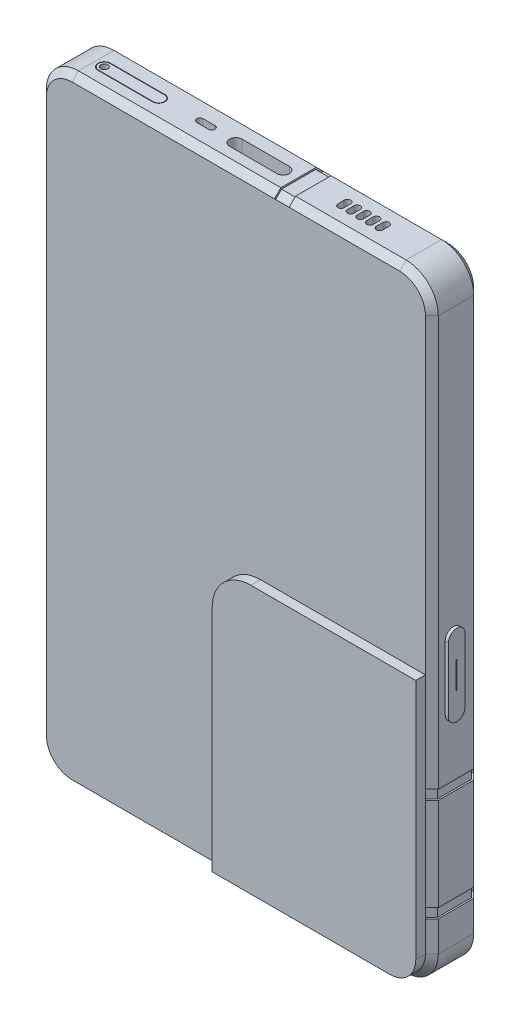
SolidWorks part; units mm, degrees
ref_plane "前视基准面" through (0, 0, 0) normal (0, 0, 1) x (1, 0, 0)
ref_plane "上视基准面" through (0, 0, 0) normal (0, 1, 0) x (1, 0, 0)
ref_plane "右视基准面" through (0, 0, 0) normal (1, 0, 0) x (0, 0, -1)
other "Configuration Table"
sketch "草图1" plane through (0, 0, 0) normal (0, 0, 1) x (1, 0, 0)
  line L1 (-50.8752, 95.8479) -> (50.8752, 95.8479)
  line L2 (-60.8752, 85.8479) -> (-60.8752, -85.8479)
  line L3 (-50.8752, -95.8479) -> (50.8752, -95.8479)
  line L4 (60.8752, 85.8479) -> (60.8752, -85.8479)
  line L5 (-60.8752, 95.8479) -> (60.8752, -95.8479) construction
  line L6 (-60.8752, -95.8479) -> (60.8752, 95.8479) construction
  arc A0 (60.8752, -85.8479) -> (50.8752, -95.8479) centre (50.8752, -85.8479) cw
  arc A1 (-50.8752, -95.8479) -> (-60.8752, -85.8479) centre (-50.8752, -85.8479) cw
  arc A2 (60.8752, 85.8479) -> (50.8752, 95.8479) centre (50.8752, 85.8479) ccw
  arc A3 (-60.8752, 85.8479) -> (-50.8752, 95.8479) centre (-50.8752, 85.8479) cw
  point P0 (0, 0)
  dimension "D1" = 10
extrude "凸台-拉伸1" add sketch "草图1" along normal blind 15
sketch "草图4" plane through (0, 95.8479, 0) normal (0, 1, 0) x (1, 0, 0)
  line L4 (25.1849, -6.5259) -> (25.1849, -8.5259)
  line L5 (27.1849, -6.5259) -> (27.1849, -8.5259)
  arc A0 (27.1849, -6.5259) -> (25.1849, -6.5259) centre (26.1849, -6.5259) ccw
  arc A1 (25.1849, -8.5259) -> (27.1849, -8.5259) centre (26.1849, -8.5259) ccw
  dimension "D1" = 2
  dimension "D2" = 2
chamfer "倒角7" distance 2 angle 45 8 edges at (60.8752, 0, 0) (57.9463, 92.919, 0) (0, 95.8479, 0) (-57.9463, 92.919, 0) (-60.8752, 0, 0) (-57.9463, -92.919, 0) (0, -95.8479, 0) (57.9463, -92.919, 0)
chamfer "倒角8" distance 2 angle 45 8 edges at (0, -95.8479, 15) (-57.9463, -92.919, 15) (-60.8752, 0, 15) (-57.9463, 92.919, 15) (0, 95.8479, 15) (57.9463, 92.919, 15) (60.8752, 0, 15) (57.9463, -92.919, 15)
extrude "切除-拉伸1" cut sketch "草图4" against normal blind 6
pattern_linear "阵列(线性)1" count 5 spacing 3 along (1, 0, 0) of "切除-拉伸1"
sketch "草图5" plane through (0, 95.8479, 0) normal (0, 1, 0) x (1, 0, 0)
  line L0 (-18.6749, -6.5259) -> (-14.9566, -6.5259)
  line L1 (-18.6749, -8.5259) -> (-14.9566, -8.5259)
  arc A0 (-18.6749, -6.5259) -> (-18.6749, -8.5259) centre (-18.6749, -7.5259) ccw
  arc A1 (-14.9566, -8.5259) -> (-14.9566, -6.5259) centre (-14.9566, -7.5259) ccw
extrude "切除-拉伸2" cut sketch "草图5" against normal blind 10
sketch "草图6" plane through (0, 95.8479, 0) normal (0, 1, 0) x (1, 0, 0)
  line L0 (-7.0941, -5.9549) -> (7.6008, -5.9549)
  line L1 (-7.0941, -9.8398) -> (7.6008, -9.8398)
  arc A0 (7.6008, -9.8398) -> (7.6008, -5.9549) centre (7.6008, -7.8973) ccw
  arc A1 (-7.0941, -5.9549) -> (-7.0941, -9.8398) centre (-7.0941, -7.8973) ccw
extrude "切除-拉伸3" cut sketch "草图6" against normal blind 40
sketch "草图7" plane through (0, 95.8479, 0) normal (0, 1, 0) x (1, 0, 0)
  line L0 (-47.9434, -5.9549) -> (-31.0508, -5.9549)
  line L2 (-47.9434, -9.8398) -> (-31.0508, -9.8398)
  arc A0 (-47.9434, -5.9549) -> (-47.9434, -9.8398) centre (-47.9434, -7.8973) ccw
  arc A2 (-31.0508, -9.8398) -> (-31.0508, -5.9549) centre (-31.0508, -7.8973) ccw
extrude "切除-拉伸5" cut sketch "草图7" against normal blind 20
sketch "草图8" plane through (0, 75.8479, 0) normal (0, 1, 0) x (1, 0, 0)
  line L0 (-47.9434, -6.108) -> (-31.0508, -6.108)
  line L2 (-31.0508, -5.9549) -> (-47.9434, -5.9549) construction
  line L3 (-47.9434, -9.6898) -> (-31.0508, -9.6898)
  line L4 (-47.9434, -9.8398) -> (-31.0508, -9.8398) construction
  arc A0 (-47.9434, -6.108) -> (-47.9434, -9.6898) centre (-47.9434, -7.8989) ccw
  arc A1 (-31.0508, -9.6898) -> (-31.0508, -6.108) centre (-31.0508, -7.8989) ccw
  dimension "D1" = 0.1531
  dimension "D2" = 0.15
extrude "凸台-拉伸2" add sketch "草图8" along normal blind 20
sketch "草图9" plane through (0, 95.8479, 0) normal (0, 1, 0) x (1, 0, 0)
  circle A0 centre (-47.9434, -7.8989) radius 1.1146
extrude "切除-拉伸6" cut sketch "草图9" against normal blind 20
sketch "草图10" plane through (0, -95.8479, 0) normal (0, -1, 0) x (1, 0, 0)
  line L0 (50.8752, 15) -> (50.8752, 0) construction
  line L1 (50.8752, 7.5) -> (-60.3841, 7.5) construction
  line L4 (-8.9454, 10.4902) -> (-20.2688, 10.4902)
  line L5 (-8.9454, 4.5098) -> (-20.2688, 4.5098)
  circle A0 centre (47.885, 7.5) radius 2.9902
  arc A3 (-20.2688, 10.4902) -> (-20.2688, 4.5098) centre (-20.2688, 7.5) ccw
  arc A4 (-8.9454, 4.5098) -> (-8.9454, 10.4902) centre (-8.9454, 7.5) ccw
extrude "切除-拉伸8" cut sketch "草图10" against normal blind 20
sketch "草图12" plane through (0, 95.8479, 0) normal (0, 1, 0) x (1, 0, 0)
  line L0 (11.9924, -2) -> (11.9924, -13)
  line L1 (50.8752, -2) -> (-50.8752, -2) construction
  line L2 (-50.8752, -13) -> (50.8752, -13) construction
  line L3 (11.9924, -13) -> (16.5529, -13)
  line L4 (16.5529, -13) -> (16.5529, -2)
  line L5 (16.5529, -2) -> (11.9924, -2)
extrude "切除-拉伸9" cut sketch "草图12" against normal blind 0.5
sketch "草图13" plane through (0, 54.424, 54.424) normal (0, 0.7071, 0.7071) x (1, 0, 0)
  line L0 (11.9924, 58.5823) -> (11.9924, 55.7539)
  line L1 (50.8752, 55.7539) -> (-50.8752, 55.7539) construction
  line L2 (11.9924, 55.7539) -> (16.5529, 55.7539)
  line L3 (16.5529, 55.7539) -> (16.5529, 58.5823)
  line L4 (16.5529, 58.5823) -> (11.9924, 58.5823)
extrude "切除-拉伸10" cut sketch "草图13" against normal blind 0.5
sketch "草图14" plane through (0, 46.924, -46.924) normal (0, 0.7071, -0.7071) x (1, 0, 0)
  line L0 (11.9924, -69.1889) -> (11.9924, -66.3605)
  line L1 (-50.8752, -66.3605) -> (50.8752, -66.3605) construction
  line L2 (11.9924, -66.3605) -> (16.5529, -66.3605)
  line L3 (16.5529, -66.3605) -> (16.5529, -69.1889)
  line L4 (16.5529, -69.1889) -> (11.9924, -69.1889)
extrude "切除-拉伸11" cut sketch "草图14" against normal blind 0.5
sketch "草图15" plane through (60.8752, 0, 0) normal (1, 0, 0) x (0, 0, -1)
  line L0 (-10.8469, -2.6673) -> (-10.8469, -22.6286)
  line L1 (-5.6844, -2.6673) -> (-5.6844, -22.6286)
  arc A0 (-5.6844, -2.6673) -> (-10.8469, -2.6673) centre (-8.2657, -2.6673) ccw
  arc A1 (-10.8469, -22.6286) -> (-5.6844, -22.6286) centre (-8.2657, -22.6286) ccw
extrude "凸台-拉伸3" add sketch "草图15" along normal blind 1
sketch "草图16" plane through (61.8752, 0, 0) normal (1, 0, 0) x (0, 0, -1)
  line L0 (-8.2657, -0.086) -> (-8.2657, -25.2099) construction
  line L1 (-8.4657, -8.6479) -> (-8.4657, -16.6479)
  line L3 (-10.8469, -12.6479) -> (-5.6844, -12.6479) construction
  line L4 (-10.8469, -2.6673) -> (-10.8469, -22.6286) construction
  line L5 (-5.6844, -22.6286) -> (-5.6844, -2.6673) construction
  line L6 (-8.0657, -8.6479) -> (-8.0657, -16.6479)
  arc A0 (-5.6844, -2.6673) -> (-10.8469, -2.6673) centre (-8.2657, -2.6673) ccw construction
  arc A1 (-10.8469, -22.6286) -> (-5.6844, -22.6286) centre (-8.2657, -22.6286) ccw construction
  arc A2 (-8.0657, -8.6479) -> (-8.4657, -8.6479) centre (-8.2657, -8.6479) ccw
  arc A3 (-8.4657, -16.6479) -> (-8.0657, -16.6479) centre (-8.2657, -16.6479) ccw
  dimension "D1" = 4
  dimension "D2" = 4
  dimension "D3" = 0.2
  dimension "D4" = 0.2
extrude "凸台-拉伸4" add sketch "草图16" along normal blind 0.1
sketch "草图17" plane through (60.8752, 0, 0) normal (1, 0, 0) x (0, 0, -1)
  line L0 (-13, -73.3596) -> (-2, -73.3596)
  line L3 (-13, 85.8479) -> (-13, -85.8479) construction
  line L4 (-2, -85.8479) -> (-2, 85.8479) construction
  line L5 (-2, -73.3596) -> (-2, -76.3596)
  line L6 (-2, -76.3596) -> (-13, -76.3596)
  line L7 (-13, -76.3596) -> (-13, -73.3596)
  line L8 (-13, -41.5134) -> (-2, -41.5134)
  line L9 (-2, -41.5134) -> (-2, -44.5134)
  line L10 (-2, -44.5134) -> (-13, -44.5134)
  line L11 (-13, -44.5134) -> (-13, -41.5134)
  dimension "D1" = 3
  dimension "D2" = 3
extrude "切除-拉伸12" cut sketch "草图17" against normal blind 0.5
sketch "草图18" plane through (29.4376, 0, -29.4376) normal (0.7071, 0, -0.7071) x (-0.7071, 0, -0.7071)
  line L0 (-44.4595, -41.5134) -> (-41.6311, -41.5134)
  line L1 (-41.6311, 85.8479) -> (-41.6311, -85.8479) construction
  line L2 (-41.6311, -41.5134) -> (-41.6311, -44.5134)
  line L3 (-41.6311, -44.5134) -> (-44.4595, -44.5134)
  line L4 (-44.4595, -44.5134) -> (-44.4595, -41.5134)
  line L5 (-44.4595, -73.3596) -> (-44.4595, -76.3596)
  line L6 (-44.4595, -76.3596) -> (-44.4595, -73.3596) construction
  line L7 (-44.4595, -76.3596) -> (-41.6311, -76.3596)
  line L8 (-41.6311, -76.3596) -> (-41.6311, -73.3596)
  line L9 (-41.6311, -73.3596) -> (-44.4595, -73.3596)
extrude "切除-拉伸13" cut sketch "草图18" against normal blind 0.5
sketch "草图19" plane through (36.9376, 0, 36.9376) normal (0.7071, 0, 0.7071) x (0.7071, 0, -0.7071)
  line L0 (33.8529, -41.5134) -> (31.0245, -41.5134)
  line L1 (31.0245, -85.8479) -> (31.0245, 85.8479) construction
  line L2 (31.0245, -41.5134) -> (31.0245, -44.5134)
  line L3 (31.0245, -44.5134) -> (33.8529, -44.5134)
  line L4 (33.8529, -44.5134) -> (33.8529, -41.5134)
  line L5 (33.8529, -73.3596) -> (31.0245, -73.3596)
  line L6 (31.0245, -73.3596) -> (31.0245, -76.3596)
  line L7 (31.0245, -76.3596) -> (33.8529, -76.3596)
  line L8 (33.8529, -76.3596) -> (33.8529, -73.3596)
extrude "切除-拉伸14" cut sketch "草图19" against normal blind 0.5
sketch "草图25" plane through (-60.8752, 0, 0) normal (-1, 0, 0) x (0, 0, 1)
  line L0 (5.0922, -20.7036) -> (5.0922, -32.7036)
  line L1 (8.6627, -20.7036) -> (8.6627, -32.7036)
  line L2 (5.0922, -37.7036) -> (5.0922, -49.7036)
  line L3 (8.6627, -37.7036) -> (8.6627, -49.7036)
  arc A0 (5.0922, -32.7036) -> (8.6627, -32.7036) centre (6.8775, -32.7036) ccw
  arc A1 (8.6627, -20.7036) -> (5.0922, -20.7036) centre (6.8775, -20.7036) ccw
  arc A2 (8.6627, -37.7036) -> (5.0922, -37.7036) centre (6.8775, -37.7036) ccw
  arc A3 (5.0922, -49.7036) -> (8.6627, -49.7036) centre (6.8775, -49.7036) ccw
  dimension "D1" = 12
  dimension "D2" = 12
  dimension "D3" = 12
  dimension "D4" = 12
  dimension "D6" = 5
extrude "凸台-拉伸5" add sketch "草图25" along normal blind 0.5
sketch "草图26" plane through (-60.8752, 0, 0) normal (-1, 0, 0) x (0, 0, 1)
  line L0 (2, -65.1421) -> (13, -65.1421)
  line L1 (2, 85.8479) -> (2, -85.8479) construction
  line L2 (13, -85.8479) -> (13, 85.8479) construction
  line L3 (13, -65.1421) -> (13, -69.1421)
  line L4 (13, -69.1421) -> (2, -69.1421)
  line L5 (2, -69.1421) -> (2, -65.1421)
  dimension "D1" = 4
extrude "切除-拉伸15" cut sketch "草图26" against normal blind 0.5
sketch "草图27" plane through (-36.9376, 0, 36.9376) normal (-0.7071, 0, 0.7071) x (0.7071, 0, 0.7071)
  line L0 (-33.8529, -65.1421) -> (-31.0245, -65.1421)
  line L1 (-31.0245, 85.8479) -> (-31.0245, -85.8479) construction
  line L2 (-31.0245, -65.1421) -> (-31.0245, -69.1421)
  line L3 (-31.0245, -69.1421) -> (-33.8529, -69.1421)
  line L4 (-33.8529, -69.1421) -> (-33.8529, -65.1421)
extrude "切除-拉伸16" cut sketch "草图27" against normal blind 0.5
sketch "草图28" plane through (-29.4376, 0, -29.4376) normal (-0.7071, 0, -0.7071) x (-0.7071, 0, 0.7071)
  line L0 (44.4595, -65.1421) -> (41.6311, -65.1421)
  line L1 (41.6311, -85.8479) -> (41.6311, 85.8479) construction
  line L2 (41.6311, -65.1421) -> (41.6311, -69.1421)
  line L3 (41.6311, -69.1421) -> (44.4595, -69.1421)
  line L4 (44.4595, -69.1421) -> (44.4595, -65.1421)
extrude "切除-拉伸17" cut sketch "草图28" against normal blind 0.5
sketch "草图30" plane through (0, 0, 15) normal (0, 0, 1) x (1, 0, 0)
  line L0 (-4.3462, -93.8479) -> (-4.3462, -22.7551)
  line L1 (-50.8752, -93.8479) -> (50.8752, -93.8479) construction
  line L2 (7.6538, -10.7551) -> (58.8752, -10.7551)
  line L3 (58.8752, -41.5134) -> (58.8752, 85.8479) construction
  line L4 (58.8752, -10.7551) -> (58.8752, -85.8479)
  line L5 (-4.3462, -93.8479) -> (50.8752, -93.8479)
  arc A0 (50.8752, -93.8479) -> (58.8752, -85.8479) centre (50.8752, -85.8479) ccw
  arc A1 (-4.3462, -22.7551) -> (7.6538, -10.7551) centre (7.6538, -22.7551) cw
  dimension "D1" = 12
extrude "凸台-拉伸6" add sketch "草图30" along normal blind 3
equation "\"0.5.000000mm\"=2"
